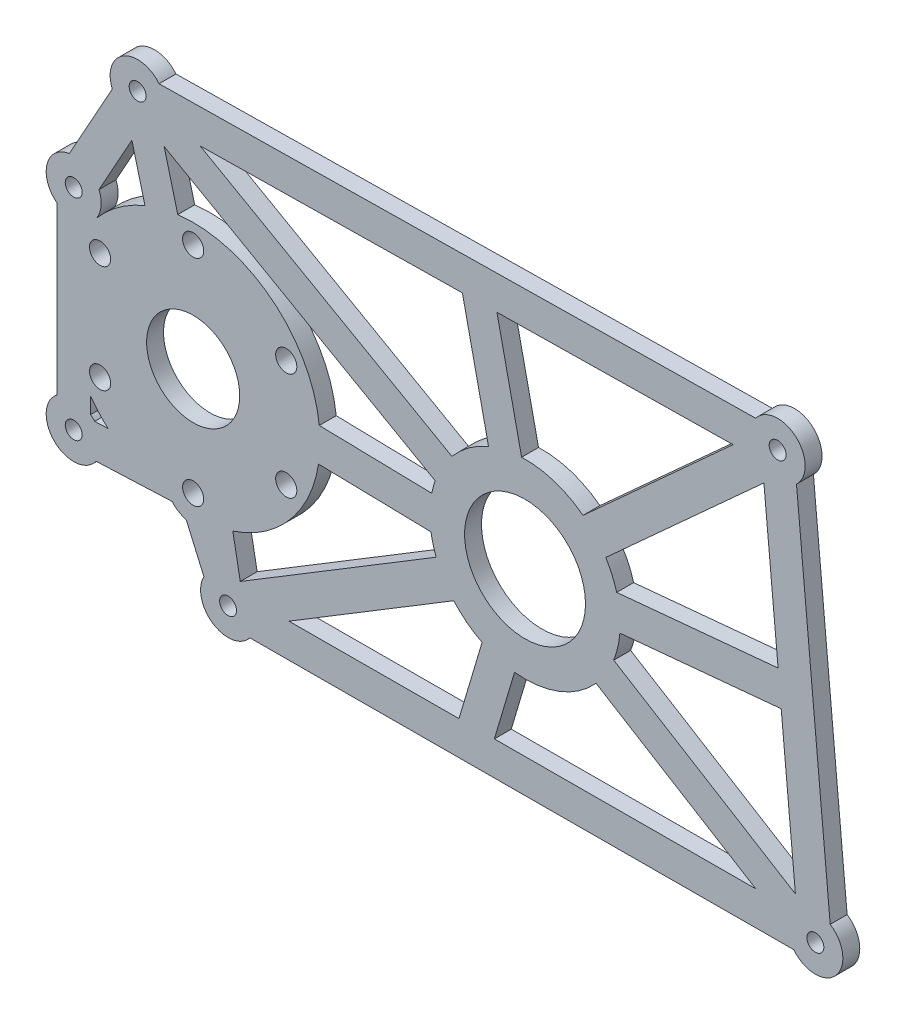
SolidWorks part; units mm, degrees
ref_plane "Front Plane" through (0, 0, 0) normal (0, 0, 1) x (1, 0, 0)
ref_plane "Top Plane" through (0, 0, 0) normal (0, 1, 0) x (1, 0, 0)
ref_plane "Right Plane" through (0, 0, 0) normal (1, 0, 0) x (0, 0, -1)
sketch "Sketch1" plane through (0, 0, 0) normal (0, 0, 1) x (1, 0, 0)
  line L15 (8.2519, 33.3618) -> (39.2181, 33.3618) construction
  line L81 (-4.8581, -43.4942) -> (-4.8581, 16.476) construction
  line L88 (39.2181, 33.3618) -> (62.4224, 33.3618) construction
  line L94 (-56.5381, 65.8828) -> (211.0649, 65.8828)
  line L95 (-56.5381, 65.8828) -> (-56.5381, -87.5703)
  line L96 (23.3772, -16.9102) -> (23.3772, -42.3102) construction
  line L97 (-56.5381, -87.5703) -> (211.0649, -87.5703)
  line L98 (211.0649, 65.8828) -> (211.0649, -87.5703)
  circle A32 centre (-4.8581, -43.4942) radius 2
  circle A46 centre (101.8113, -18.6491) radius 14.29
  circle A47 centre (31.6333, -61.2647) radius 2
  circle A52 centre (10.2519, 33.3618) radius 2
  circle A59 centre (170.4264, -60.7758) radius 2
  circle A60 centre (161.5139, 35.5525) radius 2
  circle A70 centre (-4.8581, 6.1453) radius 2
  circle A76 centre (23.3772, -42.3102) radius 2.5
  circle A81 centre (23.3772, -16.9102) radius 11
  circle A82 centre (1.3802, -29.6102) radius 2.5
  circle A83 centre (1.3802, -4.2102) radius 2.5
  circle A84 centre (23.3772, 8.4898) radius 2.5
  circle A85 centre (45.3743, -4.2102) radius 2.5
  circle A86 centre (45.3743, -29.6102) radius 2.5
  point P0 (0, 0)
  point P35 (103.8286, -4.5315)
  point P54 (23.3772, -16.9102)
  point P58 (23.3772, -16.9102)
  dimension "D1" = 4
  dimension "D5" = 28.58
  dimension "D6" = 4
  dimension "D7" = 6
  dimension "D8" = 5
  dimension "D10" = 22
  dimension "D9" = 25.4
extrude "Boss-Extrude1" add sketch "Sketch1" along normal blind 4
sketch "Sketch2" plane through (0, 0, 4) normal (0, 0, 1) x (1, 0, 0)
  line L0 (161.5139, 35.5525) -> (10.2519, 33.3618) construction
  line L1 (10.2519, 33.3618) -> (-4.8581, 6.1453) construction
  line L2 (-4.8581, 6.1453) -> (-4.8581, -43.4942) construction
  line L3 (-4.8581, -43.4942) -> (0.9858, -46.3401) construction
  line L4 (31.6333, -61.2647) -> (170.4264, -60.7758) construction
  line L5 (170.4264, -60.7758) -> (161.5139, 35.5525) construction
  line L6 (161.5139, 35.5525) -> (101.8113, -18.6491) construction
  line L7 (101.8113, -18.6491) -> (31.6333, -61.2647) construction
  line L8 (23.3772, -16.9102) -> (101.8113, -18.6491) construction
  line L9 (31.6333, -61.2647) -> (23.3772, -16.9102) construction
  line L10 (23.3772, -16.9102) -> (10.2519, 33.3618) construction
  line L11 (101.8113, -18.6491) -> (170.4264, -60.7758) construction
  line L12 (-85.224, 92.6786) -> (220.4312, 92.6786)
  line L13 (-85.224, 92.6786) -> (-85.224, -93.6131)
  line L14 (-85.224, -93.6131) -> (220.4312, -93.6131)
  line L15 (220.4312, 92.6786) -> (220.4312, -93.6131)
  line L16 (-85.224, 92.6786) -> (220.4312, -93.6131) construction
  line L17 (-85.224, -93.6131) -> (220.4312, 92.6786) construction
  line L18 (101.8113, -18.6491) -> (10.2519, 33.3618) construction
  line L19 (161.456, 39.5521) -> (7.8787, 37.3278)
  line L20 (7.8787, 37.3278) -> (-8.8581, 7.1812)
  line L21 (-8.8581, 7.1812) -> (-8.8581, -45.9954)
  line L22 (-4.8581, -43.4942) -> (23.3772, -42.3102) construction
  line L23 (161.5718, 31.5529) -> (12.6252, 29.3957)
  line L24 (12.6252, 29.3957) -> (-0.8581, 5.1094)
  line L25 (-0.8581, 5.1094) -> (-0.8581, -40.993)
  line L26 (23.3772, -42.3102) -> (31.6333, -61.2647) construction
  line L27 (174.4094, -60.4072) -> (165.0249, 41.0227)
  line L28 (162.6186, 41.958) -> (99.1227, -15.6875)
  line L29 (31.6473, -65.2646) -> (170.4405, -64.7757)
  line L30 (99.7185, -22.0579) -> (168.3335, -64.1846)
  line L31 (99.7352, -15.2301) -> (29.5571, -57.8457)
  line L32 (35.5657, -60.5327) -> (27.3097, -16.1782)
  line L33 (23.2886, -20.9092) -> (101.7227, -22.6481)
  line L34 (27.2475, -15.8997) -> (16.5161, 25.203)
  line L35 (99.8356, -22.1271) -> (16.5161, 25.203)
  line L36 (166.4434, -61.1443) -> (158.2692, 27.2043)
  line L37 (158.2692, 27.2043) -> (104.5, -21.6106)
  line L38 (27.7008, -61.9966) -> (19.4448, -17.6422) construction
  line L39 (103.9042, -15.2403) -> (172.5192, -57.367)
  line L40 (103.8875, -22.068) -> (33.7094, -64.6836)
  line L41 (26.7632, -56.9597) -> (19.4448, -17.6422)
  line L42 (23.4659, -12.9112) -> (101.9, -14.65)
  line L43 (19.5069, -17.9207) -> (5.0874, 37.3086)
  line L44 (103.7871, -15.171) -> (7.7727, 39.3704)
  line L45 (101.8113, -18.6491) -> (165.9701, -12.6116) construction
  line L46 (102.1861, -22.6315) -> (166.3449, -16.594)
  line L47 (101.4366, -14.6666) -> (165.5954, -8.6292)
  line L48 (19.5069, -17.9207) -> (3.9877, 41.5205) construction
  line L49 (103.7871, -15.171) -> (3.9877, 41.5205) construction
  line L50 (164.7586, 43.9008) -> (99.1227, -15.6875) construction
  line L51 (174.4094, -60.4072) -> (164.7586, 43.9008) construction
  line L52 (-4.6905, -47.4907) -> (20.805, -46.4216)
  line L53 (-8.8581, -45.9954) -> (29.882, -64.8609) construction
  line L54 (25.7894, -58.4188) -> (31.6333, -61.2647) construction
  line L55 (-4.8581, -43.4942) -> (31.6333, -61.2647) construction
  line L56 (20.805, -46.4216) -> (27.966, -62.862)
  line L57 (-0.8581, -40.993) -> (33.3845, -57.6684) construction
  line L58 (34.9552, -57.2529) -> (170.4123, -56.7758)
  line L59 (-5.0257, -39.4977) -> (25.9494, -38.1988)
  line L60 (25.9494, -38.1988) -> (35.3005, -59.6673)
  line L61 (101.8113, -18.6491) -> (90.2211, 34.52) construction
  line L62 (101.8113, -18.6491) -> (89.1919, -61.0619) construction
  line L63 (97.9775, -17.5083) -> (85.358, -59.9212)
  line L64 (105.6452, -19.7898) -> (93.0258, -62.2026)
  line L65 (105.7196, -17.7971) -> (94.1293, 35.3719)
  line L66 (97.9031, -19.501) -> (86.3128, 33.668)
  circle A0 centre (161.5139, 35.5525) radius 6.5
  circle A1 centre (170.4264, -60.7758) radius 6.5
  circle A2 centre (31.6333, -61.2647) radius 6.5
  circle A3 centre (-4.8581, -43.4942) radius 6.5
  circle A4 centre (-4.8581, 6.1453) radius 6.5
  circle A5 centre (23.3772, -16.9102) radius 30
  circle A6 centre (10.2519, 33.3618) radius 6.5
  circle A7 centre (101.8113, -18.6491) radius 22.5
  circle A8 centre (23.3772, -42.3102) radius 6.5
  point P24 (67.6036, -0.4672)
  dimension "D1" = 13
  dimension "D2" = 45
  dimension "D3" = 60
  dimension "D10" = 13
  dimension "D4" = 4
  dimension "D5" = 4
  dimension "D6" = 4
  dimension "D7" = 4
  dimension "D8" = 4
  dimension "D9" = 4
  dimension "D11" = 4
  dimension "D12" = 4
  dimension "D13" = 4
  dimension "D14" = 4
  dimension "D15" = 4
  dimension "D16" = 4
sketch "Sketch3" plane through (0, 0, 4) normal (0, 0, 1) x (1, 0, 0)
  line L1 (183.3704, 49.7896) -> (-38.0291, 49.7896)
  line L2 (183.3704, 49.7896) -> (183.3704, -70.3617)
  line L3 (183.3704, -70.3617) -> (-38.0291, -70.3617)
  line L4 (-38.0291, 49.7896) -> (-38.0291, -70.3617)
extrude "Cut-Extrude8" cut sketch "Sketch2" against normal blind 10 contours L15 L12 L13 L14 A8 L52 A3 L21 A4 L20 A6 L19 A0 L27 A1 L29 A2 L56 | A7 L66 L23 L44 | A7 L28 L23 L65 | A7 L47 L36 L37 | A7 L39 L36 L46 | A7 L64 L58 L30 | A7 L40 L58 L63 | A7 L33 A5 L32 L31 | A7 L35 L34 A5 L42 | A5 L43 L24 A4 | A5 L25 A3 L59
